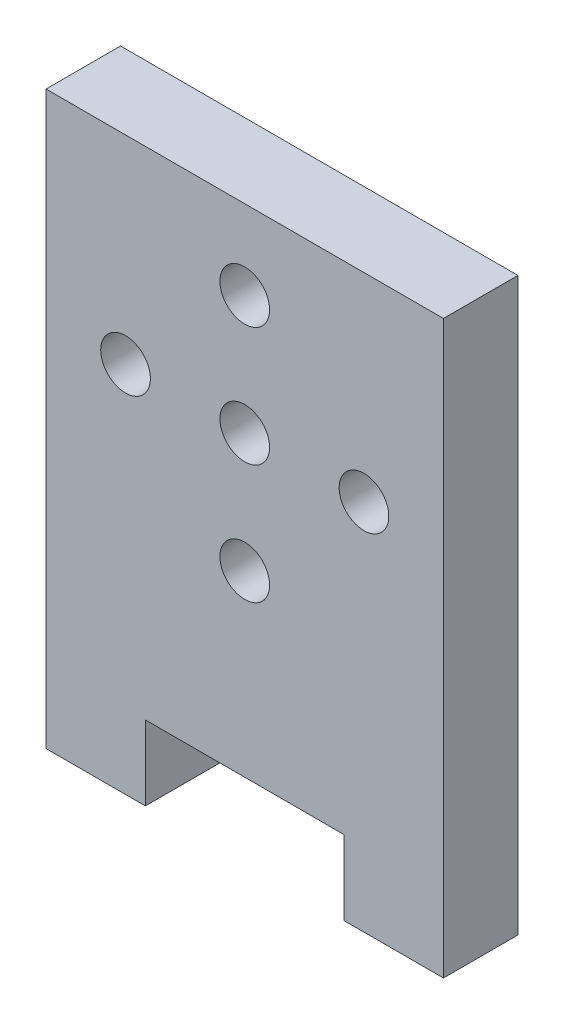
SolidWorks part; units mm, degrees
ref_plane "Front Plane" through (0, 0, 0) normal (0, 0, 1) x (1, 0, 0)
ref_plane "Top Plane" through (0, 0, 0) normal (0, 1, 0) x (1, 0, 0)
ref_plane "Right Plane" through (0, 0, 0) normal (1, 0, 0) x (0, 0, -1)
sketch "Sketch1" plane through (0, 0, 0) normal (0, 0, 1) x (1, 0, 0)
  line L0 (0, 0) -> (12.7, 0)
  line L1 (12.7, 0) -> (12.7, -4.7625)
  line L2 (12.7, -4.7625) -> (19.05, -4.7625)
  line L3 (19.05, -4.7625) -> (19.05, 31.75)
  line L4 (19.05, 31.75) -> (-6.35, 31.75)
  line L5 (-6.35, 31.75) -> (-6.35, -4.7625)
  line L6 (-6.35, -4.7625) -> (0, -4.7625)
  line L7 (0, -4.7625) -> (0, 0)
  line L8 (6.35, 19.05) -> (6.35, 26.67) construction
  line L9 (13.97, 19.05) -> (6.35, 19.05) construction
  line L10 (6.35, 11.43) -> (6.35, 19.05) construction
  line L11 (-1.27, 19.05) -> (6.35, 19.05) construction
  circle A0 centre (6.35, 19.05) radius 1.5875
  circle A1 centre (6.35, 26.67) radius 1.5875
  circle A2 centre (13.97, 19.05) radius 1.5875
  circle A3 centre (-1.27, 19.05) radius 1.5875
  circle A4 centre (6.35, 11.43) radius 1.5875
  dimension "D2" = 3.175
  dimension "D3" = 3.175
  dimension "D1" = 6.35
  dimension "D4" = 12.7
  dimension "D5" = 4.7625
  dimension "D6" = 7.62
  dimension "D7" = 19.05
  dimension "D8" = 31.75
extrude "Boss-Extrude1" add sketch "Sketch1" along normal blind 4.7625
